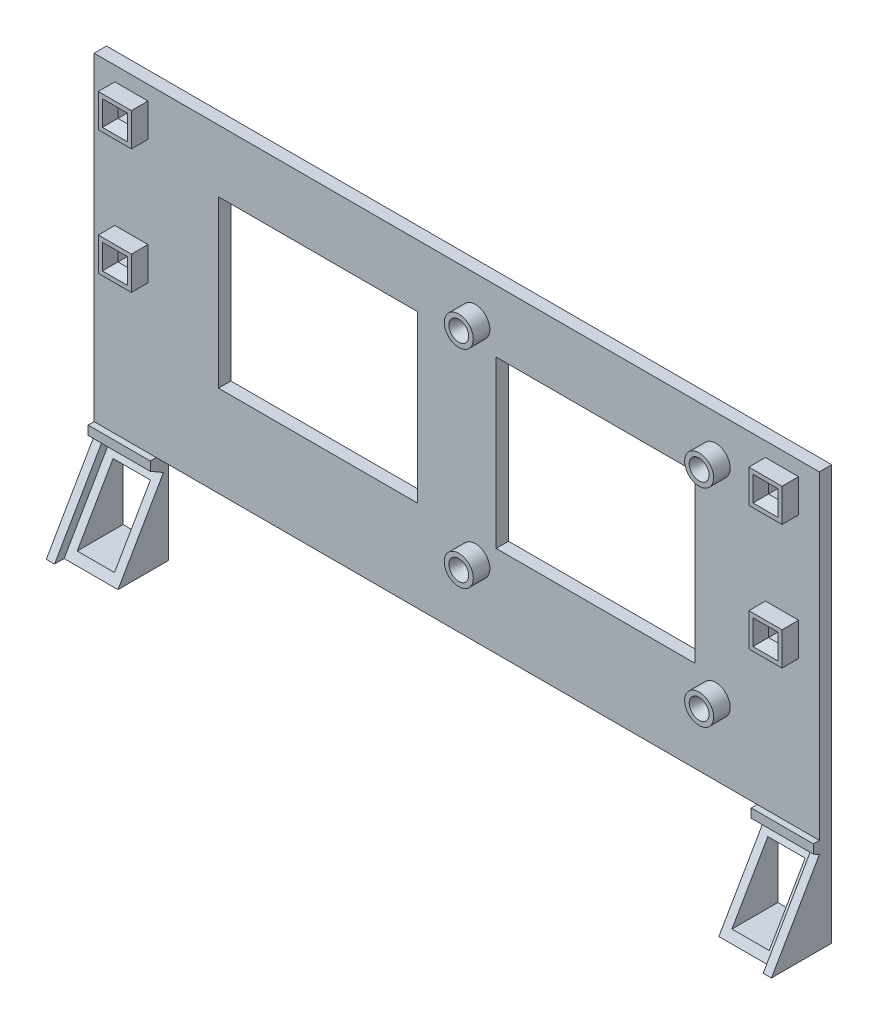
SolidWorks part; units mm, degrees
ref_plane "前视基准面" through (0, 0, 0) normal (0, 0, 1) x (1, 0, 0)
ref_plane "上视基准面" through (0, 0, 0) normal (0, 1, 0) x (1, 0, 0)
ref_plane "右视基准面" through (0, 0, 0) normal (1, 0, 0) x (0, 0, -1)
sketch "草图1" plane through (0, 0, 0) normal (0, 0, 1) x (1, 0, 0)
  line L1 (-135.2519, 42.1854) -> (39.7481, 42.1854)
  line L2 (-135.2519, 42.1854) -> (-135.2519, -57.8146)
  line L3 (-135.2519, -57.8146) -> (39.7481, -57.8146)
  line L4 (39.7481, 42.1854) -> (39.7481, -57.8146)
  dimension "D1" = 175
  dimension "D2" = 100
extrude "凸台-拉伸1" add sketch "草图1" along normal blind 3
sketch "草图3" plane through (-135.2519, 0, 0) normal (-1, 0, 0) x (0, 0, 1)
  line L0 (3, -57.8146) -> (14.547, -57.8146)
  line L1 (14.547, -57.8146) -> (3, -37.8146)
  line L2 (3, 42.1854) -> (3, -57.8146) construction
  line L3 (3, -37.8146) -> (3, -57.8146)
  dimension "D1" = 20
  dimension "D2" = 30
extrude "凸台-拉伸3" add sketch "草图3" against normal through all
sketch "草图5" plane through (-135.2519, 0, 0) normal (-1, 0, 0) x (0, 0, 1)
  line L0 (3, -37.8146) -> (3, -34.8146)
  line L1 (3, 42.1854) -> (3, -37.8146) construction
  line L2 (3, -34.8146) -> (8.1962, -34.8146)
  line L3 (8.1962, -34.8146) -> (3, -37.8146)
  dimension "D1" = 3
  dimension "D2" = 60
extrude "凸台-拉伸4" add sketch "草图5" against normal through all
sketch "草图7" plane through (-135.2519, 0, 0) normal (-1, 0, 0) x (0, 0, 1)
  line L1 (8.8398, -33.5513) -> (4.4513, -33.5513)
  line L2 (8.8398, -33.5513) -> (8.8398, -37.7429)
  line L3 (8.8398, -37.7429) -> (4.4513, -37.7429)
  line L4 (4.4513, -33.5513) -> (4.4513, -37.7429)
extrude "切除-拉伸3" cut sketch "草图7" against normal through all
sketch "草图8" plane through (0, -8.1546, -14.1242) normal (0, 0.5, 0.866) x (1, 0, 0)
  line L0 (39.7481, -57.3424) -> (-135.2519, -57.3424) construction
  line L1 (-133.2519, -57.3424) -> (37.7481, -57.3424)
  line L2 (-133.2519, -57.3424) -> (-133.2519, -34.2484)
  line L3 (-133.2519, -34.2484) -> (37.7481, -34.2484)
  line L4 (37.7481, -57.3424) -> (37.7481, -34.2484)
  line L5 (39.7481, -34.2484) -> (-135.2519, -34.2484) construction
  line L6 (-135.2519, -57.3424) -> (-135.2519, -34.2484) construction
  line L7 (39.7481, -57.3424) -> (39.7481, -34.2484) construction
  dimension "D1" = 2
  dimension "D2" = 2
extrude "切除-拉伸4" cut sketch "草图8" against normal blind 2 contours L2 L3 L4 L1
sketch "草图2" plane through (0, 0, 3) normal (0, 0, 1) x (1, 0, 0)
  line L1 (39.7481, 42.1854) -> (-135.2519, 42.1854) construction
  line L2 (39.7481, -34.8146) -> (39.7481, 42.1854) construction
  circle A0 centre (-43.2519, 32.1854) radius 1.4
  circle A1 centre (14.7481, 32.1854) radius 1.4
  circle A2 centre (14.7481, -17.8146) radius 1.4
  circle A3 centre (-43.2519, -17.8146) radius 1.4
  dimension "D1" = 2.8
  dimension "D2" = 2.8
  dimension "D3" = 2.8
  dimension "D4" = 2.8
  dimension "D5" = 58
  dimension "D6" = 58
  dimension "D7" = 50
  dimension "D8" = 10
  dimension "D9" = 25
sketch "草图10" plane through (0, 0, 3) normal (0, 0, 1) x (1, 0, 0)
  line L0 (-135.2519, 42.1854) -> (-135.2519, -34.8146) construction
  line L1 (-130.2519, 38.6854) -> (-122.2519, 38.6854)
  line L2 (-130.2519, 38.6854) -> (-130.2519, 30.6854)
  line L3 (-130.2519, 30.6854) -> (-122.2519, 30.6854)
  line L4 (-122.2519, 38.6854) -> (-122.2519, 30.6854)
  line L5 (39.7481, 42.1854) -> (-135.2519, 42.1854) construction
  line L6 (26.7481, 38.6854) -> (26.7481, 30.6854)
  line L7 (26.7481, 38.6854) -> (34.7481, 38.6854)
  line L8 (34.7481, 38.6854) -> (34.7481, 30.6854)
  line L9 (26.7481, 30.6854) -> (34.7481, 30.6854)
  line L10 (-130.2519, 38.6854) -> (26.7481, 38.6854) construction
  line L11 (39.7481, -34.8146) -> (39.7481, 42.1854) construction
  line L12 (-130.2519, 8.6854) -> (-130.2519, 0.6854)
  line L13 (-130.2519, 8.6854) -> (-122.2519, 8.6854)
  line L14 (-122.2519, 8.6854) -> (-122.2519, 0.6854)
  line L15 (-130.2519, 0.6854) -> (-122.2519, 0.6854)
  line L16 (26.7481, 8.6854) -> (26.7481, 0.6854)
  line L17 (26.7481, 0.6854) -> (34.7481, 0.6854)
  line L18 (34.7481, 8.6854) -> (34.7481, 0.6854)
  line L19 (26.7481, 8.6854) -> (34.7481, 8.6854)
  line L20 (-130.2519, 38.6854) -> (-130.2519, 8.6854) construction
  circle A0 centre (-43.2519, 32.1854) radius 3.5
  circle A1 centre (14.7481, 32.1854) radius 3.5
  circle A2 centre (-43.2519, -17.8146) radius 3.5
  circle A3 centre (14.7481, -17.8146) radius 3.5
  dimension "D1" = 8
  dimension "D2" = 8
  dimension "D3" = 5
  dimension "D4" = 3.5
  dimension "D6" = 157
  dimension "D7" = 5
  dimension "D9" = 30
  dimension "D5" = 2
  dimension "D8" = 2
extrude "凸台-拉伸6" add sketch "草图10" along normal blind 4
extrude "切除-拉伸6" cut sketch "草图2" against normal through all and the other way through all contours A0 | A1 | A3 | A2
sketch "草图11" plane through (0, -57.8146, 0) normal (0, -1, 0) x (1, 0, 0)
  line L0 (-133.2519, 12.2376) -> (37.7481, 12.2376) construction
  line L1 (-120.2519, 12.2376) -> (24.7481, 12.2376)
  line L2 (-120.2519, 12.2376) -> (-120.2519, 0)
  line L3 (-120.2519, 0) -> (24.7481, 0)
  line L4 (24.7481, 12.2376) -> (24.7481, 0)
  line L5 (-135.2519, 0) -> (39.7481, 0) construction
  line L6 (-135.2519, 14.547) -> (-135.2519, 0) construction
  line L7 (39.7481, 14.547) -> (39.7481, 0) construction
  point P12 (-120.2519, 12.2376)
  dimension "D1" = 15
  dimension "D2" = 15
extrude "切除-拉伸7" cut sketch "草图11" against normal blind 23 contours L2 L3 L4 L1
sketch "草图12" plane through (-135.2519, 0, 0) normal (-1, 0, 0) x (0, 0, 1)
  line L0 (14.547, -57.8146) -> (3, -37.8146)
  line L1 (14.547, -57.8146) -> (123.6662, 5.1854)
  line L2 (3, -37.8146) -> (112.1192, 25.1854)
  line L3 (123.6662, 5.1854) -> (112.1192, 25.1854)
  dimension "D1" = 126
sketch "草图13" plane through (0, 0, 7) normal (0, 0, 1) x (1, 0, 0)
  line L0 (-130.2519, 38.6854) -> (-130.2519, 30.6854) construction
  line L1 (-128.2519, 36.6854) -> (-124.2519, 36.6854)
  line L2 (-128.2519, 36.6854) -> (-128.2519, 32.6854)
  line L3 (-128.2519, 32.6854) -> (-124.2519, 32.6854)
  line L4 (-124.2519, 36.6854) -> (-124.2519, 32.6854)
  line L5 (-122.2519, 38.6854) -> (-130.2519, 38.6854) construction
  line L6 (39.7481, 42.1854) -> (-135.2519, 42.1854) construction
  line L7 (-135.2519, 42.1854) -> (-135.2519, -34.8146) construction
  line L8 (28.7481, 36.6854) -> (28.7481, 32.6854)
  line L13 (28.7481, 36.6854) -> (32.7481, 36.6854)
  line L14 (32.7481, 36.6854) -> (32.7481, 32.6854)
  line L15 (28.7481, 32.6854) -> (32.7481, 32.6854)
  line L16 (-128.2519, 36.6854) -> (28.7481, 36.6854) construction
  line L17 (34.7481, 30.6854) -> (34.7481, 38.6854) construction
  line L18 (34.7481, 38.6854) -> (26.7481, 38.6854) construction
  line L19 (-128.2519, 6.6854) -> (-128.2519, 2.6854)
  line L20 (-128.2519, 6.6854) -> (-124.2519, 6.6854)
  line L21 (-124.2519, 6.6854) -> (-124.2519, 2.6854)
  line L22 (-128.2519, 2.6854) -> (-124.2519, 2.6854)
  line L23 (28.7481, 6.6854) -> (28.7481, 2.6854)
  line L24 (28.7481, 2.6854) -> (32.7481, 2.6854)
  line L25 (32.7481, 6.6854) -> (32.7481, 2.6854)
  line L26 (28.7481, 6.6854) -> (32.7481, 6.6854)
  line L27 (-128.2519, 36.6854) -> (-128.2519, 6.6854) construction
  point P20 (34.7481, 34.6854)
  point P23 (30.7481, 38.6854)
  dimension "D1" = 2
  dimension "D2" = 2
  dimension "D3" = 4
  dimension "D4" = 4
  dimension "D5" = 5.5
  dimension "D6" = 7
  dimension "D8" = 157
  dimension "D9" = 2
  dimension "D10" = 2
  dimension "D12" = 30
  dimension "D7" = 2
  dimension "D11" = 2
extrude "切除-拉伸8" cut sketch "草图13" against normal through all
chamfer "倒角1" distance 1 angle 70 20 edges at (-126.2519, 2.6854, 7) (-124.2519, 4.6854, 7) (-126.2519, 6.6854, 7) (-128.2519, 4.6854, 7) (16.1481, -17.8146, 7) (-41.8519, -17.8146, 7) (-41.8519, 32.1854, 7) (16.1481, 32.1854, 7) (30.7481, 2.6854, 7) (32.7481, 4.6854, 7) (28.7481, 4.6854, 7) (30.7481, 6.6854, 7) (30.7481, 32.6854, 7) (32.7481, 34.6854, 7) (28.7481, 34.6854, 7) (30.7481, 36.6854, 7) (-126.2519, 32.6854, 7) (-124.2519, 34.6854, 7) (-126.2519, 36.6854, 7) (-128.2519, 34.6854, 7)
sketch "草图14" plane through (-135.2519, 0, 0) normal (-1, 0, 0) x (0, 0, 1)
  line L0 (0, 42.1854) -> (0, -57.8146) construction
  line L1 (0, 36.6854) -> (80, 36.6854)
  line L2 (0, 36.6854) -> (0, 32.6854)
  line L3 (0, 32.6854) -> (7, 32.6854)
  line L5 (3, 42.1854) -> (0, 42.1854) construction
  line L6 (7, 38.6854) -> (7, 30.6854) construction
  line L7 (0, 6.6854) -> (7, 6.6854)
  line L8 (0, 6.6854) -> (0, 2.6854)
  line L9 (0, 2.6854) -> (25.2007, 2.6854)
  line L12 (7, 32.6854) -> (7, 6.6854)
  line L14 (11, 32.6854) -> (11, 6.6854)
  line L15 (25.2007, 2.6854) -> (56.7474, 32.6854)
  line L18 (23.6024, 6.6854) -> (50.9429, 32.6854)
  line L19 (80, 36.6854) -> (92.5094, 15.0184)
  line L22 (77.6906, 32.6854) -> (89.5453, 12.1524)
  line L23 (3, -37.8146) -> (112.1192, 25.1854) construction
  line L25 (89.5453, 12.1524) -> (90.5453, 10.4204)
  line L26 (93.0094, 14.1524) -> (94.0094, 12.4204)
  line L27 (90.5453, 10.4204) -> (94.0094, 12.4204)
  line L29 (93.0094, 14.1524) -> (93.8755, 14.6524)
  line L30 (92.5094, 15.0184) -> (93.3755, 15.5184)
  line L31 (93.8755, 14.6524) -> (93.3755, 15.5184)
  line L32 (11, 32.6854) -> (50.9429, 32.6854)
  line L33 (11, 6.6854) -> (23.6024, 6.6854)
  line L34 (56.7474, 32.6854) -> (77.6906, 32.6854)
  dimension "D1" = 4
  dimension "D2" = 5.5
  dimension "D3" = 4
  dimension "D4" = 26
  dimension "D5" = 80
  dimension "D6" = 4
  dimension "D7" = 0
  dimension "D8" = 120
  dimension "D9" = 26.0189
  dimension "D10" = 2
  dimension "D11" = 1
  dimension "D12" = 1
  dimension "D13" = 23.7095
  dimension "D14" = 4
  dimension "D15" = 20.9432
  dimension "D16" = 43.5339
  dimension "D17" = 25.2007
sketch "草图15" plane through (0, 0, 3) normal (0, 0, 1) x (1, 0, 0)
  line L0 (-105.2519, 27.1854) -> (-105.2519, -12.8146)
  line L1 (-38.2519, 27.1854) -> (9.7481, 27.1854)
  line L2 (-38.2519, 27.1854) -> (-38.2519, -12.8146)
  line L3 (-38.2519, -12.8146) -> (9.7481, -12.8146)
  line L4 (9.7481, 27.1854) -> (9.7481, -12.8146)
  line L5 (-105.2519, 27.1854) -> (-57.2519, 27.1854)
  line L6 (-57.2519, 27.1854) -> (-57.2519, -12.8146)
  line L7 (-105.2519, -12.8146) -> (-57.2519, -12.8146)
  line L8 (-38.2519, 27.1854) -> (-105.2519, 27.1854) construction
  line L9 (-133.2519, -57.8146) -> (-120.2519, -57.8146) construction
  line L10 (-131.2519, -55.8146) -> (-122.2519, -55.8146)
  line L11 (-131.2519, -55.8146) -> (-131.2519, -40.8146)
  line L12 (-131.2519, -40.8146) -> (-122.2519, -40.8146)
  line L13 (-122.2519, -55.8146) -> (-122.2519, -40.8146)
  line L14 (-133.2519, -38.8146) -> (-120.2519, -38.8146) construction
  line L15 (-120.2519, -38.8146) -> (-120.2519, -57.8146) construction
  line L16 (-133.2519, -57.8146) -> (-133.2519, -38.8146) construction
  line L17 (24.7481, -57.8146) -> (37.7481, -57.8146) construction
  line L18 (26.7481, -40.8146) -> (35.7481, -40.8146)
  line L19 (26.7481, -40.8146) -> (26.7481, -55.8146)
  line L20 (26.7481, -55.8146) -> (35.7481, -55.8146)
  line L21 (35.7481, -40.8146) -> (35.7481, -55.8146)
  line L22 (24.7481, -38.8146) -> (37.7481, -38.8146) construction
  line L23 (24.7481, -38.8146) -> (24.7481, -57.8146) construction
  line L24 (37.7481, -57.8146) -> (37.7481, -38.8146) construction
  line L25 (-135.2519, -57.8146) -> (-135.2519, 5.1854) construction
  line L26 (39.7481, -34.8146) -> (39.7481, 42.1854) construction
  circle A0 centre (14.7481, 32.1854) radius 1.4 construction
  circle A1 centre (-43.2519, 32.1854) radius 1.4 construction
  circle A2 centre (14.7481, -17.8146) radius 1.4 construction
  point P44 (0, 0)
  dimension "D1" = 5
  dimension "D2" = 5
  dimension "D3" = 5
  dimension "D4" = 5
  dimension "D6" = 67
  dimension "D7" = 2
  dimension "D8" = 2
  dimension "D9" = 2
  dimension "D10" = 2
  dimension "D11" = 2
  dimension "D12" = 2
  dimension "D13" = 2
  dimension "D14" = 2
  dimension "D15" = 30
  dimension "D16" = 30
  dimension "D5" = 2
extrude "切除-拉伸9" cut sketch "草图15" against normal through all both and the other way through all
